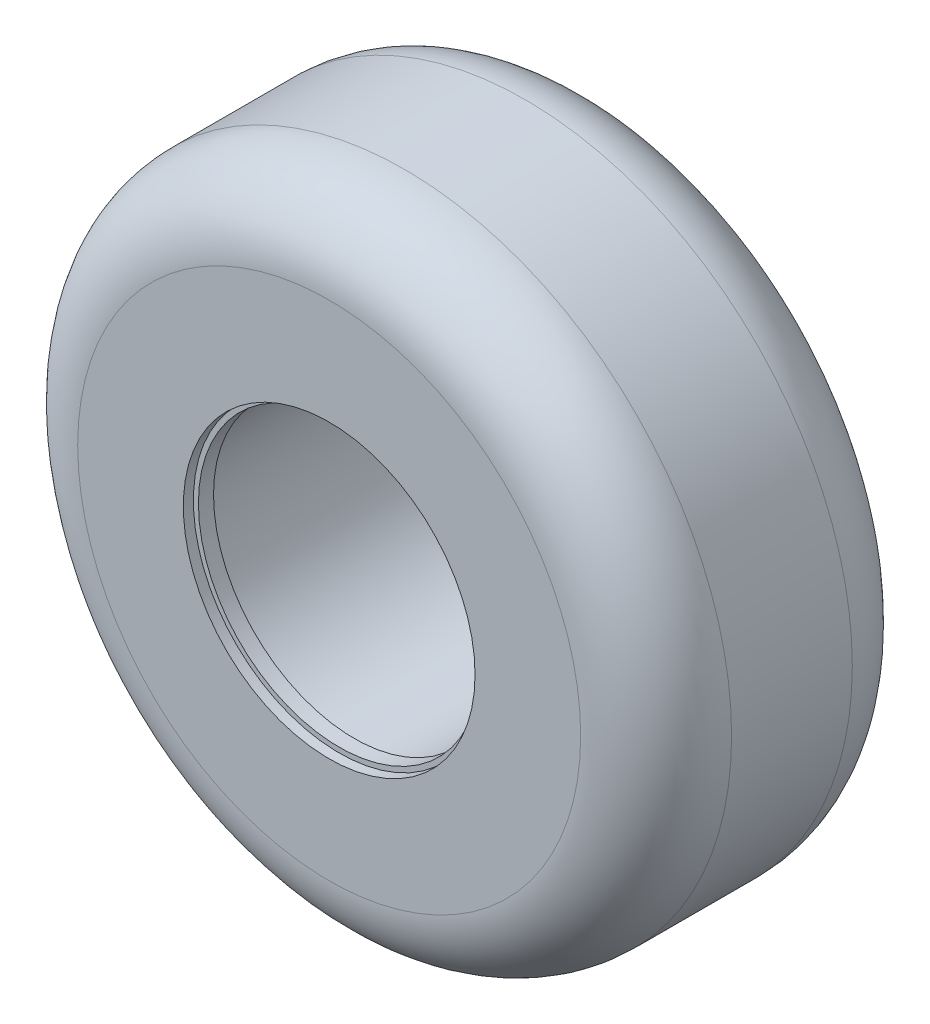
SolidWorks part; units mm, degrees
ref_plane "前视基准面" through (0, 0, 0) normal (0, 0, 1) x (1, 0, 0)
ref_plane "上视基准面" through (0, 0, 0) normal (0, 1, 0) x (1, 0, 0)
ref_plane "右视基准面" through (0, 0, 0) normal (1, 0, 0) x (0, 0, -1)
sketch "草图1" plane through (0, 0, 0) normal (0, 0, 1) x (1, 0, 0)
  circle A0 centre (0, 0) radius 65
  circle A1 centre (0, 0) radius 28
  dimension "D1" = 130
  dimension "D2" = 56
extrude "凸台-拉伸1" add sketch "草图1" along normal blind 54
sketch "草图2" plane through (0, 0, 0) normal (0, 0, -1) x (-1, 0, 0)
  circle A0 centre (0, 0) radius 29
  dimension "D1" = 58
extrude "切除-拉伸1" cut sketch "草图2" against normal blind 2
sketch "草图3" plane through (0, 0, 54) normal (0, 0, 1) x (1, 0, 0)
  circle A0 centre (0, 0) radius 29
  dimension "D1" = 58
extrude "切除-拉伸2" cut sketch "草图3" against normal blind 2
sketch "草图4" plane through (0, 0, 0) normal (0, 1, 0) x (1, 0, 0)
  line L0 (0, 0) -> (0, -54) construction
  line L1 (29, 0) -> (-29, 0) construction
  line L2 (-29, -54) -> (29, -54) construction
  line L3 (-65, 0) -> (-65, -54)
  line L4 (65, 0) -> (-65, 0) construction
  line L5 (-65, -54) -> (65, -54) construction
  line L6 (-65, -27) -> (0, -27) construction
  line L8 (-28.5174, -5) -> (-27.5174, -5)
  line L9 (-28.5174, -5) -> (-28.5174, -49)
  line L10 (-28.5174, -49) -> (-27.5174, -49)
  line L11 (-27.5174, -5) -> (-27.5174, -49)
  line L12 (-28.5174, -5) -> (-27.5174, -49) construction
  line L13 (-28.5174, -49) -> (-27.5174, -5) construction
  point P14 (-28.0174, -27)
  dimension "D1" = 44
  dimension "D2" = 1
revolve "切除-旋转1" cut sketch "草图4" angle 360 about L0
fillet "圆角1" radius 15 2 edges at (65, 0, 54) (65, 0, 0)
